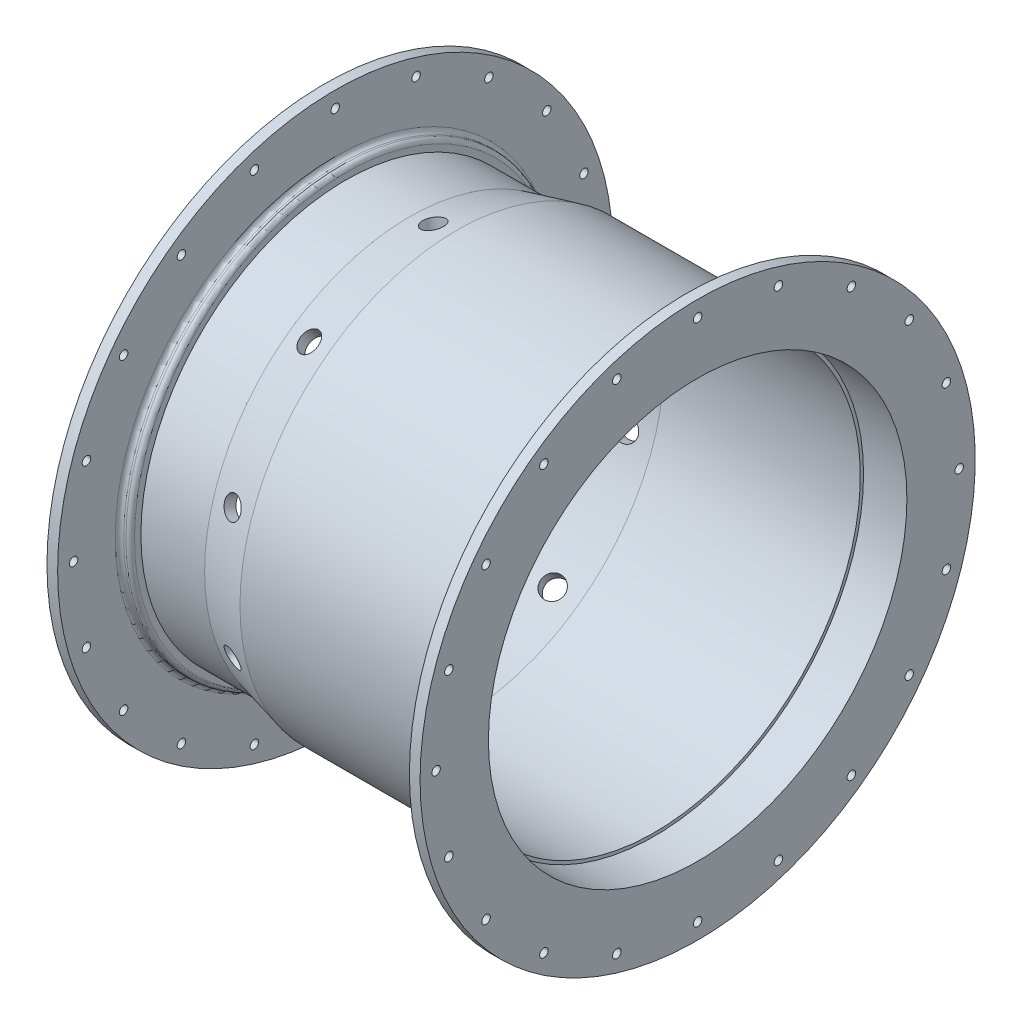
SolidWorks part; units mm, degrees
ref_plane "Front Plane" through (0, 0, 0) normal (0, 0, 1) x (1, 0, 0)
ref_plane "Top Plane" through (0, 0, 0) normal (0, 1, 0) x (1, 0, 0)
ref_plane "Right Plane" through (0, 0, 0) normal (1, 0, 0) x (0, 0, -1)
sketch "Sketch1" plane through (0, 0, 0) normal (0, 0, 1) x (1, 0, 0)
  line L0 (-81.0013, 0) -> (108.0739, 0) construction
  line L1 (112.25, 130) -> (107.25, 130)
  line L2 (107.25, 130) -> (107.25, 101.5)
  line L3 (107.25, 101.5) -> (-0.6144, 101.5)
  line L4 (-0.6144, 101.5) -> (-22.6544, 96)
  line L5 (-22.6544, 96) -> (-52.5, 96)
  line L6 (-52.5, 96) -> (-52.5, 101)
  line L7 (-52.5, 101) -> (-57.5, 101)
  line L8 (-57.5, 101) -> (-57.5, 130)
  line L9 (-57.5, 130) -> (-62.5, 130)
  line L10 (-62.5, 130) -> (-62.5, 97)
  line L11 (-62.5, 97) -> (-57.5, 97)
  line L12 (-57.5, 97) -> (-57.5, 85)
  line L14 (-22.04, 91) -> (0, 96.5)
  line L15 (0, 96.5) -> (91.95, 96.5)
  line L16 (91.95, 96.5) -> (91.95, 98)
  line L17 (91.95, 98) -> (112.25, 98)
  line L18 (112.25, 98) -> (112.25, 130)
  line L19 (-57.5, 85) -> (-42.3, 85)
  line L20 (-42.3, 85) -> (-42.3, 91)
  line L21 (-42.3, 91) -> (-22.04, 91)
  point P3 (-11.02, 93.75)
  point P17 (0, 0)
  point P25 (0, 0)
  point P26 (0, 0)
  point P27 (0, 0)
  point P28 (0, 0)
  point P29 (0, 0)
  point P30 (0, 0)
  point P31 (0, 0)
  point P32 (0, 0)
  point P33 (0, 0)
  point P34 (0, 0)
  point P35 (0, 0)
  point P36 (0, 0)
  point P37 (0, 0)
  dimension "D1" = 174.75
  dimension "D2" = 62.5
  dimension "D3" = 5
  dimension "D4" = 5
  dimension "D5" = 20.3
  dimension "D6" = 1.5
  dimension "D8" = 5
  dimension "D9" = 5
  dimension "D10" = 6
  dimension "D11" = 15.2
  dimension "D12" = 33
  dimension "D13" = 22.04
  dimension "D14" = 130
  dimension "D15" = 101.5
  dimension "D16" = 85
revolve "Revolve1" add sketch "Sketch1" angle 360 about L0
sketch "Sketch2" plane through (0, 0, 0) normal (0, 0, 1) x (1, 0, 0)
  line L0 (-0.6144, 101.5) -> (-0.6144, 132.944) construction
  line L1 (-0.6144, 101.5) -> (-22.6544, 96) construction
  line L2 (-0.6144, 101.5) -> (-22.6544, 96) construction
  line L3 (-11.6344, 98.75) -> (-17.4652, 131.8181) construction
  line L4 (-12.2699, 102.3536) -> (-17.1939, 101.4853)
  line L5 (-17.1939, 101.4853) -> (-15.0026, 89.058)
  line L6 (-15.0026, 89.058) -> (-10.0786, 89.9262)
  line L7 (-10.0786, 89.9262) -> (-12.2699, 102.3536)
  dimension "D1" = 10
  dimension "D2" = 4
  dimension "D3" = 5
revolve "Cut-Revolve1" cut sketch "Sketch2" angle 360 about L3
pattern_circular "CirPattern2" count 10 over 360 about axis through (-57.5, 0, 0) along (-1, 0, 0) of "Cut-Revolve1"
sketch "Sketch3" plane through (-62.5, 0, 0) normal (-1, 0, 0) x (0, 0, 1)
  circle A0 centre (0, 122.5) radius 2
  dimension "D1" = 4
  dimension "D2" = 122.5
extrude "Cut-Extrude1" cut sketch "Sketch3" against normal through all
pattern_circular "CirPattern3" count 20 over 360 about axis through (0, 0, 0) along (1, 0, 0) of "Cut-Extrude1"
fillet "Fillet1" radius 2 3 edges at (107.25, 0, 101.5) (-57.5, 0, 101) (-52.5, 0, 101)
